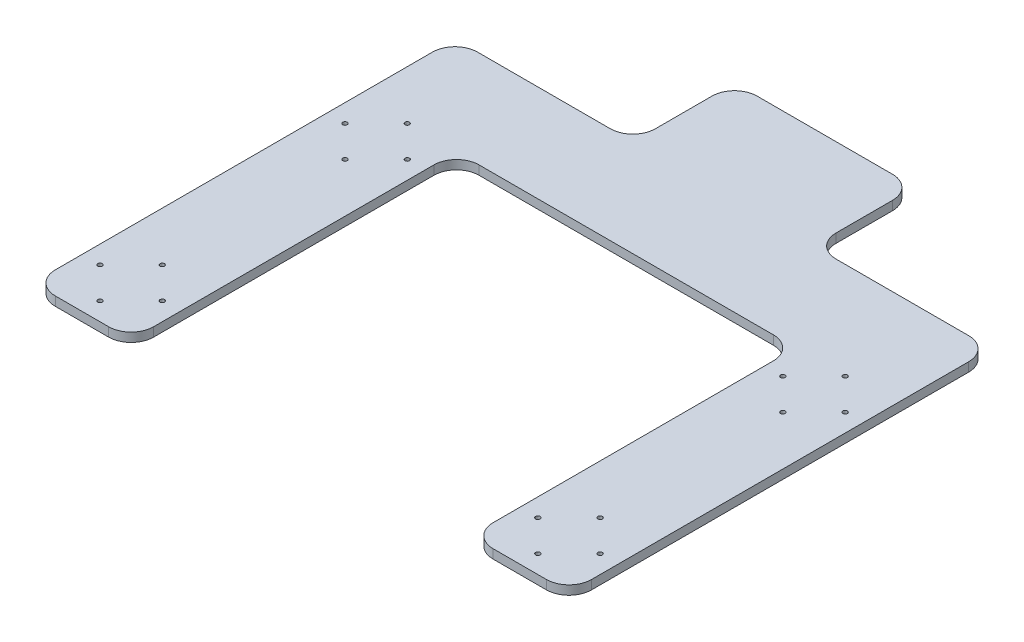
SolidWorks part; units mm, degrees
ref_plane "Front Plane" through (0, 0, 0) normal (0, 0, 1) x (1, 0, 0)
ref_plane "Top Plane" through (0, 0, 0) normal (0, 1, 0) x (1, 0, 0)
ref_plane "Right Plane" through (0, 0, 0) normal (1, 0, 0) x (0, 0, -1)
sketch "Sketch3" plane through (0, 0, 0) normal (0, 1, 0) x (1, 0, 0)
  line L0 (-75.438, 48.3095) -> (-75.438, -99.1095)
  line L1 (-75.438, -99.1095) -> (-47.752, -99.1095)
  line L2 (-47.752, -99.1095) -> (-47.752, 3.5101)
  line L3 (-47.752, 3.5101) -> (-47.752, 43.2295)
  line L4 (47.752, 3.5101) -> (47.752, -99.1095)
  line L5 (47.752, -99.1095) -> (75.438, -99.1095)
  line L6 (75.438, -99.1095) -> (75.438, 48.3095)
  line L7 (-25.4, 99.1095) -> (-25.4, 70.503)
  line L8 (-25.4, 70.503) -> (-75.438, 70.503)
  line L9 (25.4, 99.1095) -> (-25.4, 99.1095)
  line L10 (-75.438, 70.503) -> (-75.438, 48.3095)
  line L11 (25.4, 99.1095) -> (25.4, 70.503)
  line L12 (-61.595, 43.2295) -> (-61.595, 25.7035) construction
  line L13 (-70.358, 34.4665) -> (-52.832, 34.4665) construction
  line L14 (0, 0) -> (0, 99.1095) construction
  line L15 (-25.4, 99.1095) -> (-25.4, -99.1095) construction
  line L16 (-25.4, -99.1095) -> (-47.752, -99.1095) construction
  line L17 (-25.4, 0) -> (0, 0) construction
  line L18 (-70.358, -34.4665) -> (-52.832, -34.4665) construction
  line L19 (-61.595, -43.2295) -> (-61.595, -25.7035) construction
  line L20 (61.595, -43.2295) -> (61.595, -25.7035) construction
  line L21 (70.358, -34.4665) -> (52.832, -34.4665) construction
  line L22 (70.358, 34.4665) -> (52.832, 34.4665) construction
  line L23 (61.595, 43.2295) -> (61.595, 25.7035) construction
  line L24 (25.4, 70.503) -> (75.438, 70.503)
  line L25 (75.438, 70.503) -> (75.438, 48.3095)
  line L26 (-47.752, 43.2295) -> (47.752, 43.2295)
  line L27 (47.752, 43.2295) -> (47.752, 3.5101)
  circle A0 centre (-61.595, 43.2295) radius 0.635
  circle A1 centre (-70.358, 34.4665) radius 0.635
  circle A2 centre (-61.595, 25.7035) radius 0.635
  circle A3 centre (-52.832, 34.4665) radius 0.635
  circle A4 centre (-52.832, -34.4665) radius 0.635
  circle A5 centre (-61.595, -25.7035) radius 0.635
  circle A6 centre (-70.358, -34.4665) radius 0.635
  circle A7 centre (-61.595, -43.2295) radius 0.635
  circle A8 centre (61.595, -43.2295) radius 0.635
  circle A9 centre (61.595, -25.7035) radius 0.635
  circle A10 centre (52.832, -34.4665) radius 0.635
  circle A11 centre (52.832, 34.4665) radius 0.635
  circle A12 centre (61.595, 25.7035) radius 0.635
  circle A13 centre (61.595, 43.2295) radius 0.635
  circle A14 centre (70.358, -34.4665) radius 0.635
  circle A15 centre (70.358, 34.4665) radius 0.635
  point P16 (-61.595, 34.4665)
  point P34 (-61.595, -34.4665)
  point P42 (61.595, -34.4665)
  point P50 (61.595, 34.4665)
  dimension "D2" = 1.27
  dimension "D9" = 1.27
  dimension "D10" = 1.27
  dimension "D1" = 17.526
  dimension "D3" = 5.08
  dimension "D6" = 50.8
  dimension "D7" = 61.595
  dimension "D8" = 34.4665
  dimension "D11" = 5.08
extrude "Boss-Extrude2" add sketch "Sketch3" along normal blind 2.54
sketch "Sketch4" plane through (0, 2.54, 0) normal (0, 1, 0) x (1, 0, 0)
  line L1 (-79.1273, -48.3095) -> (86.1526, -48.3095)
  line L2 (-79.1273, -48.3095) -> (-79.1273, -175.3095)
  line L3 (-79.1273, -175.3095) -> (86.1526, -175.3095)
  line L4 (86.1526, -48.3095) -> (86.1526, -175.3095)
  circle A0 centre (-61.595, -43.2295) radius 0.635 construction
  circle A1 centre (-61.595, -43.2295) radius 0.635 construction
  dimension "D1" = 5.08
  dimension "D4" = 127
extrude "Cut-Extrude1" cut sketch "Sketch4" against normal through all
fillet "Fillet3" radius 6.35 12 edges at (-75.438, 1.27, -70.503) (-75.438, 1.27, 48.3095) (-47.752, 1.27, -43.2295) (47.752, 1.27, -43.2295) (47.752, 1.27, 48.3095) (-47.752, 1.27, 48.3095) (75.438, 1.27, 48.3095) (75.438, 1.27, -70.503) (25.4, 1.27, -70.503) (25.4, 1.27, -99.1095) (-25.4, 1.27, -99.1095) (-25.4, 1.27, -70.503)
equation "\"D11@Sketch3\" = \"D3@Sketch3\""
